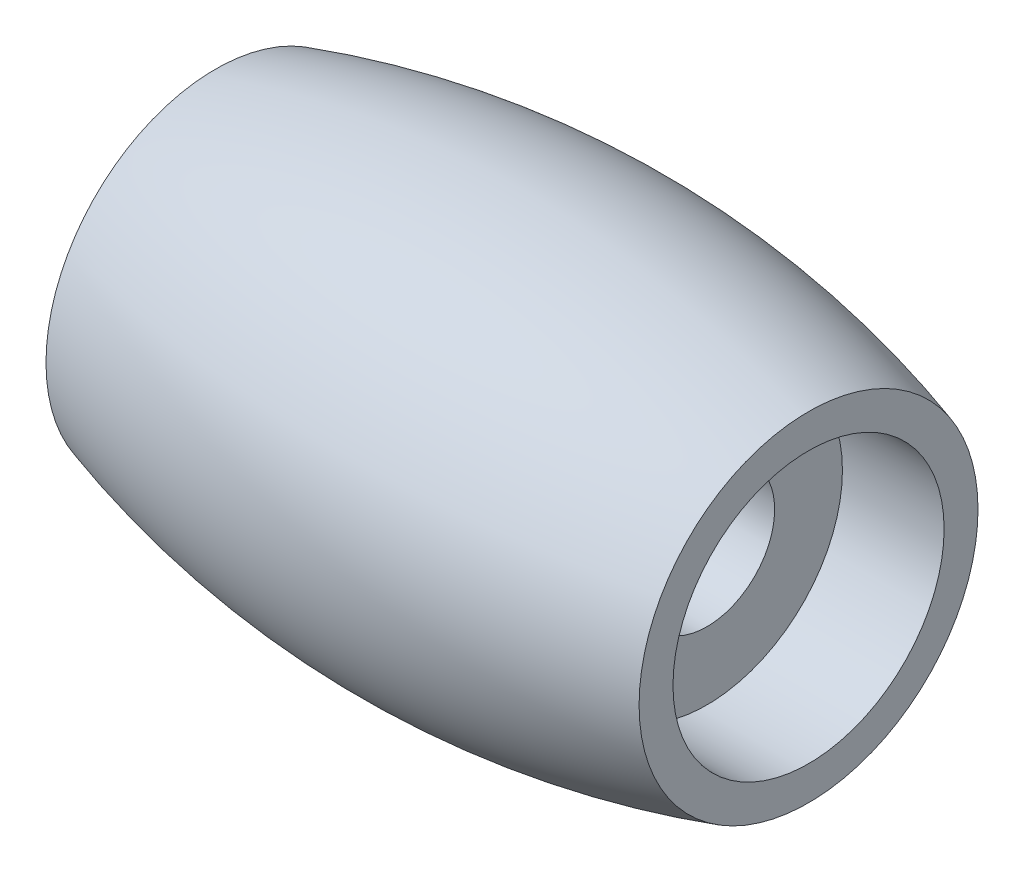
SolidWorks part; units mm, degrees
ref_plane "Front Plane" through (0, 0, 0) normal (0, 0, 1) x (1, 0, 0)
ref_plane "Top Plane" through (0, 0, 0) normal (0, 1, 0) x (1, 0, 0)
ref_plane "Right Plane" through (0, 0, 0) normal (1, 0, 0) x (0, 0, -1)
sketch "Sketch2" plane through (0, 0, 0) normal (0, 0, 1) x (1, 0, 0)
  line L0 (0, 6.5859) -> (0, -8.2148) construction
  line L1 (-8.918, 0) -> (11.5313, 0) construction
  line L2 (-2.875, 1) -> (2.875, 1)
  line L3 (2.875, 1) -> (2.875, 2)
  line L4 (2.875, 2) -> (4.375, 2)
  line L5 (4.375, 2) -> (4.375, 2.5)
  line L6 (-4.375, 2) -> (-4.375, 2.5)
  line L7 (-2.875, 2) -> (-4.375, 2)
  line L8 (-2.875, 1) -> (-2.875, 2)
  arc A0 (-4.375, 2.5) -> (4.375, 2.5) centre (0, -11.8478) cw
  point P18 (0, 1)
  dimension "D6" = 15
  dimension "D1" = 1
  dimension "D2" = 1.5
  dimension "D3" = 2
  dimension "D4" = 2.5
  dimension "D5" = 4.375
revolve "Revolve1" add sketch "Sketch2" angle 360 about L1
